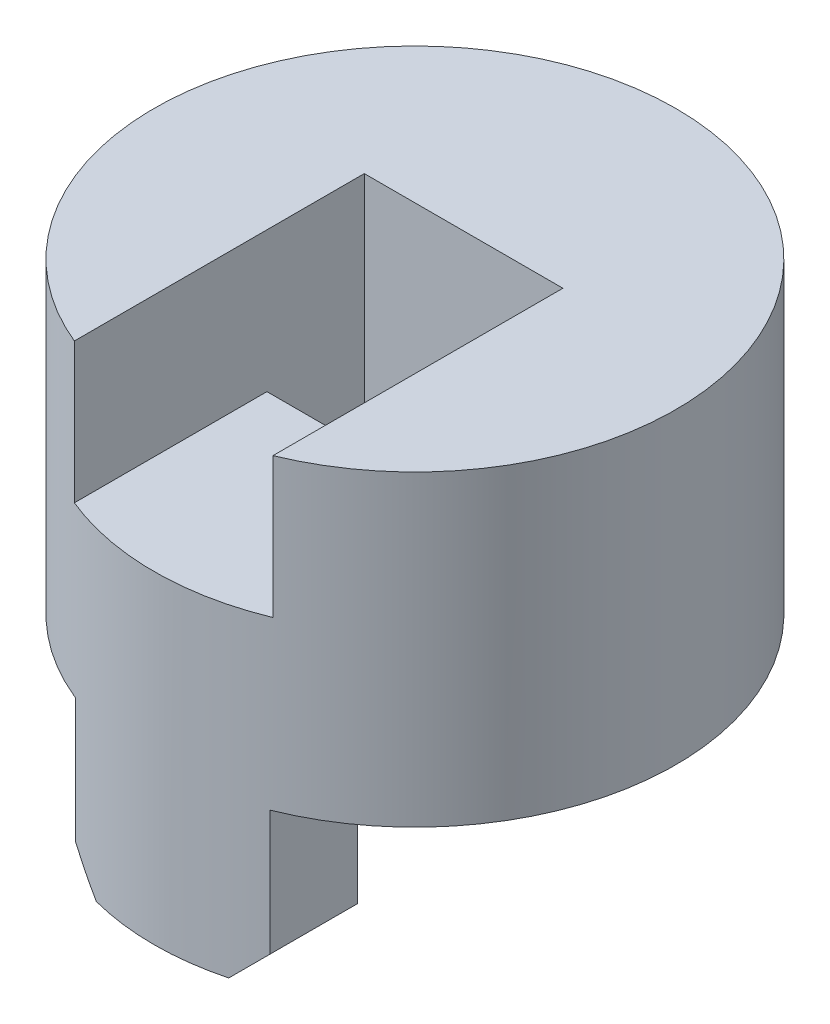
SolidWorks part; units mm, degrees
ref_plane "Front Plane" through (0, 0, 0) normal (0, 0, 1) x (1, 0, 0)
ref_plane "Top Plane" through (0, 0, 0) normal (0, 1, 0) x (1, 0, 0)
ref_plane "Right Plane" through (0, 0, 0) normal (1, 0, 0) x (0, 0, -1)
sketch "Sketch1" plane through (0, 0, 0) normal (0, 1, 0) x (1, 0, 0)
  circle A0 centre (0, 0) radius 3.45
  dimension "D1" = 6.9
extrude "Boss-Extrude1" add sketch "Sketch1" along normal blind 1.1
sketch "Sketch2" plane through (0, 1.1, 0) normal (0, 1, 0) x (1, 0, 0)
  circle A0 centre (0, 0) radius 6.7
  dimension "D1" = 13.4
extrude "Boss-Extrude2" add sketch "Sketch2" along normal blind 4.3
sketch "Sketch3" plane through (0, 5.4, 0) normal (0, 1, 0) x (1, 0, 0)
  line L1 (-2.55, -1.25) -> (2.55, -1.25)
  line L2 (-2.55, -1.25) -> (-2.55, 1.25)
  line L3 (-2.55, 1.25) -> (2.55, 1.25)
  line L4 (2.55, -1.25) -> (2.55, 1.25)
  line L5 (-2.55, -1.25) -> (2.55, 1.25) construction
  line L6 (-2.55, 1.25) -> (2.55, -1.25) construction
  point P0 (0, 0)
  dimension "D1" = 5.1
  dimension "D2" = 2.5
extrude "Cut-Extrude1" cut sketch "Sketch3" against normal through all
sketch "Sketch4" plane through (0, 1.1, 0) normal (0, -1, 0) x (1, 0, 0)
  line L1 (-2.5, -7.5188) -> (2.5, -7.5188)
  line L2 (-2.5, -7.5188) -> (-2.5, 7.5188)
  line L3 (-2.5, 7.5188) -> (2.5, 7.5188)
  line L4 (2.5, -7.5188) -> (2.5, 7.5188)
  line L5 (-2.5, -7.5188) -> (2.5, 7.5188) construction
  line L6 (-2.5, 7.5188) -> (2.5, -7.5188) construction
  circle A0 centre (0, 0) radius 4.7
  circle A1 centre (0, 0) radius 6.7 construction
  circle A2 centre (0, 0) radius 6.7
  circle M3 centre (0, 0) radius 6.7
  dimension "D1" = 9.4
  dimension "D2" = 5
extrude "Boss-Extrude3" add sketch "Sketch4" along normal blind 4 contours A0 L4 L2 M3
chamfer "Chamfer1" distance 0.8 angle 45 2 edges at (2.5, -2.9, 5.098) (-2.5, -2.9, 5.098)
sketch "Sketch5" plane through (0, 5.4, 0) normal (0, 1, 0) x (1, 0, 0)
  line L0 (2.55, -1.25) -> (2.55, 1.25) construction
  line L1 (-2.55, 1.25) -> (2.55, 1.25)
  line L2 (-2.55, 1.25) -> (-2.55, -9.1144)
  line L3 (-2.55, -9.1144) -> (2.55, -9.1144)
  line L4 (2.55, 1.25) -> (2.55, -9.1144)
  circle A0 centre (0, 0) radius 6.7 construction
  circle A1 centre (0, 0) radius 6.7
  line M2 (2.55, 1.25) -> (2.55, -1.25)
  line M4 (-2.55, -1.25) -> (-2.55, 1.25)
  line M5 (-2.55, 1.25) -> (2.55, 1.25)
  circle M6 centre (0, 0) radius 6.7
extrude "Boss-Extrude4" add sketch "Sketch5" along normal offset from surface (3.6 mm away) 7.9 contours L4 L2 M2 M6 M4 M5
